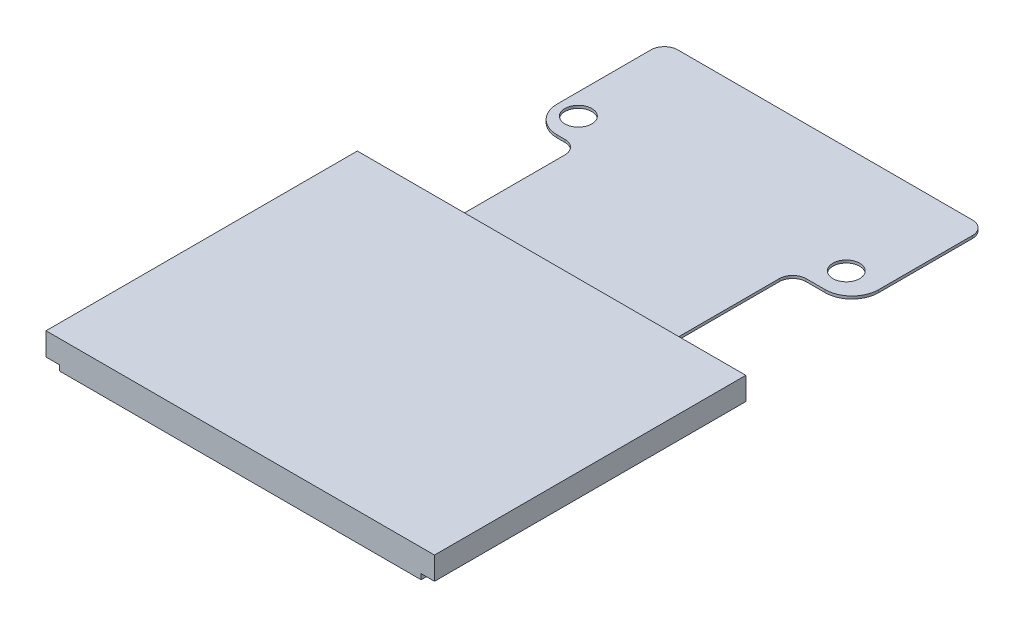
SolidWorks part; units mm, degrees
other "DetailItem6"
ref_plane "Front Plane" through (0, 0, 0) normal (0, 0, 1) x (1, 0, 0)
ref_plane "Top Plane" through (0, 0, 0) normal (0, 1, 0) x (1, 0, 0)
ref_plane "Right Plane" through (0, 0, 0) normal (1, 0, 0) x (0, 0, -1)
sketch "Sketch2" plane through (0, 0, 0) normal (0, 1, 0) x (1, 0, 0)
  line L1 (-7.25, 5.81) -> (7.25, 5.81)
  line L2 (-7.25, 5.81) -> (-7.25, -5.81)
  line L3 (-7.25, -5.81) -> (7.25, -5.81)
  line L4 (7.25, 5.81) -> (7.25, -5.81)
  line L5 (-7.25, 5.81) -> (7.25, -5.81) construction
  line L6 (-7.25, -5.81) -> (7.25, 5.81) construction
  point P0 (0, 0)
extrude "Boss-Extrude1" add sketch "Sketch2" along normal mid plane 0.85
sketch "Sketch6" plane through (0, -0.425, 0) normal (0, -1, 0) x (1, 0, 0)
  line L0 (-7.25, 5.81) -> (7.25, 5.81) construction
  line L1 (-6.75, 5.81) -> (6.75, 5.81)
  line L2 (-6.75, 5.81) -> (-6.75, -2.29)
  line L3 (-6.75, -2.29) -> (6.75, -2.29)
  line L4 (6.75, 5.81) -> (6.75, -2.29)
  line L5 (-6.75, 5.81) -> (6.75, -2.29) construction
  line L6 (-6.75, -2.29) -> (6.75, 5.81) construction
  point P0 (0, 1.76)
  dimension "D1" = 0
  dimension "D2" = 0
extrude "Boss-Extrude2" add sketch "Sketch6" along normal blind 0.2
sketch "Sketch7" plane through (0, -0.625, 0) normal (0, -1, 0) x (1, 0, 0)
  line L0 (6.75, 5.81) -> (-6.75, 5.81) construction
  line L1 (-6.29, 5) -> (6.29, 5)
  line L2 (-6.29, 5) -> (-6.29, -1.98)
  line L3 (-6.29, -1.98) -> (6.29, -1.98)
  line L4 (6.29, 5) -> (6.29, -1.98)
  line L5 (-6.29, 5) -> (6.29, -1.98) construction
  line L6 (-6.29, -1.98) -> (6.29, 5) construction
  point P0 (0, 1.51)
  dimension "D1" = 0.81
  dimension "D2" = 0
extrude "Boss-Extrude3" add sketch "Sketch7" along normal blind 0.15
sketch "Sketch9" plane through (0, -0.425, 0) normal (0, -1, 0) x (1, 0, 0)
  line L1 (-6.096, -2.4527) -> (6.096, -2.4527)
  line L2 (-6.096, -2.4527) -> (-6.096, -4.9927)
  line L3 (-6.096, -4.9927) -> (-3.2893, -4.9927)
  line L4 (6.096, -2.4527) -> (6.096, -4.9927)
  line L5 (-6.096, -2.4527) -> (6.096, -4.9927) construction
  line L6 (-6.096, -4.9927) -> (6.096, -2.4527) construction
  line L7 (-6.75, -2.29) -> (6.75, -2.29) construction
  line L8 (-3.2893, -7.8563) -> (3.2893, -7.8563)
  line L9 (-3.2893, -4.9927) -> (-3.2893, -7.8563)
  line L10 (0, 0) -> (0, -4.9927) construction
  line L11 (3.2893, -4.9927) -> (3.2893, -7.8563)
  line L12 (3.2893, -4.9927) -> (6.096, -4.9927)
  line L13 (0, -7.8563) -> (0, -11.701) construction
  point P0 (0, -3.7227)
  point P11 (0, -7.8563)
  dimension "D1" = 0.1627
  dimension "D2" = 12.192
  dimension "D3" = 0
  dimension "D4" = 2.54
  dimension "D5" = 2.8636
  dimension "D6" = 6.5786
extrude "Boss-Extrude4" add sketch "Sketch9" along normal blind 0.1755
fillet "Fillet1" radius 0.762 2 edges at (6.096, -0.5127, -4.9927) (-6.096, -0.5127, -4.9927)
fillet "Fillet2" radius 0.2 2 edges at (3.2893, -0.5127, -7.8563) (-3.2893, -0.5127, -7.8563)
sketch "Sketch13" plane through (0, 0, -5.81) normal (0, 0, -1) x (-1, 0, 0)
  line L0 (-3.2893, -0.425) -> (3.2893, -0.425) construction
  line L2 (-4, -0.425) -> (-4, -0.325)
  line L3 (-4, -0.325) -> (4, -0.325)
  line L4 (4, -0.425) -> (4, -0.325)
  line L5 (0, -0.425) -> (4, -0.325) construction
  line L6 (-4, -0.325) -> (0, -0.425) construction
  line L7 (-4, -0.425) -> (4, -0.425)
  point P0 (0, -0.425)
  dimension "D1" = 0.1
  dimension "D2" = 0
  dimension "D3" = 8
  dimension "D4" = 4
extrude "Boss-Extrude5" add sketch "Sketch13" along normal blind 10
sketch "Sketch20" plane through (0, -0.425, 0) normal (0, -1, 0) x (1, 0, 0)
  line L1 (-4, -15.81) -> (-5.79, -15.81)
  line L2 (-4, -15.81) -> (-4, -10.81)
  line L3 (-4, -10.81) -> (-5.79, -10.81)
  line L4 (-5.79, -15.81) -> (-5.79, -10.81)
  line L5 (4, -15.81) -> (6.21, -15.81)
  line L6 (4, -15.81) -> (4, -10.81)
  line L7 (4, -10.81) -> (6.21, -10.81)
  line L8 (6.21, -15.81) -> (6.21, -10.81)
  dimension "D1" = 5
  dimension "D2" = 5
extrude "Boss-Extrude6" add sketch "Sketch20" against normal blind 0.1
sketch "Sketch23" plane through (0, -0.325, 0) normal (0, 1, 0) x (1, 0, 0)
  line L0 (-5.79, 15.81) -> (6.21, 15.81) construction
  line L1 (0, -0.66) -> (0, 0.66) construction
  circle A0 centre (5, 11.81) radius 0.5
  circle A1 centre (-5, 11.81) radius 0.5
  dimension "D1" = 4
  dimension "D2" = 4
  dimension "D3" = 5
  dimension "D4" = 5
extrude "Cut-Extrude1" cut sketch "Sketch23" against normal blind 0.1
fillet "Fillet3" radius 1 2 edges at (-5.79, -0.375, -10.81) (6.21, -0.375, -10.81)
fillet "Fillet4" radius 0.5 2 edges at (6.21, -0.375, -15.81) (-5.79, -0.375, -15.81)
fillet "Fillet5" radius 0.5 2 edges at (4, -0.375, -10.81) (-4, -0.375, -10.81)
sketch "Sketch18" plane through (0, 0, 0) normal (0, 1, 0) x (1, 0, 0)
  line L1 (-7.25, 5.81) -> (8.2424, 5.81)
  line L2 (-7.25, 5.81) -> (-7.25, 14.0621)
  line L3 (-7.25, 14.0621) -> (8.2424, 14.0621)
  line L4 (8.2424, 5.81) -> (8.2424, 14.0621)
sketch "Sketch19" plane through (0, 0, 0) normal (0, 1, 0) x (1, 0, 0)
  point P0 (-8.0411, 2.7398)
  point P1 (-2.0019, 15.0104)
  point P2 (9.0884, 2.7398)
  point P3 (9.0884, -2.9976)
